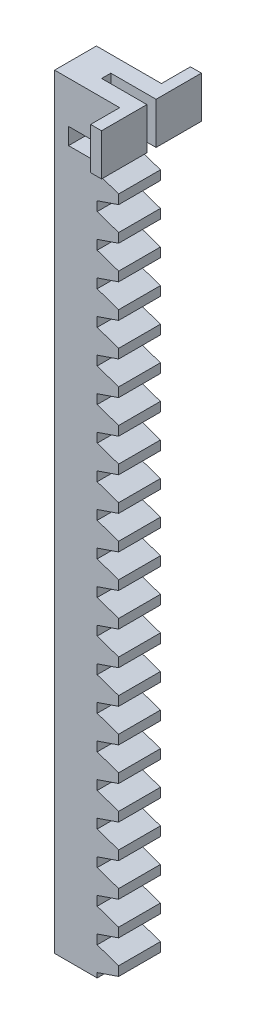
SolidWorks part; units mm, degrees
ref_plane "Plano frontal" through (0, 0, 0) normal (0, 0, 1) x (1, 0, 0)
ref_plane "Plano superior" through (0, 0, 0) normal (0, 1, 0) x (1, 0, 0)
ref_plane "Plano direito" through (0, 0, 0) normal (1, 0, 0) x (0, 0, -1)
sketch "Esboço1" plane through (0, 0, 0) normal (0, 0, 1) x (1, 0, 0)
  line L0 (-2.5965, -162.8747) -> (2.5465, -161.1158)
  line L1 (2.5465, -161.1158) -> (2.5465, -158.8842)
  line L2 (2.5465, -158.8842) -> (-2.5965, -157.1253)
  line L3 (-2.5965, -157.1253) -> (-2.5965, -154.8747)
  line L4 (-2.5965, -154.8747) -> (2.5465, -153.1158)
  line L5 (2.5465, -153.1158) -> (2.5465, -150.8842)
  line L6 (2.5465, -150.8842) -> (-2.5965, -149.1253)
  line L7 (-2.5965, -149.1253) -> (-2.5965, -146.8747)
  line L8 (-2.5965, -146.8747) -> (2.5465, -145.1158)
  line L9 (2.5465, -145.1158) -> (2.5465, -142.8842)
  line L10 (2.5465, -142.8842) -> (-2.5965, -141.1253)
  line L11 (-2.5965, -141.1253) -> (-2.5965, -138.8747)
  line L12 (-2.5965, -138.8747) -> (2.5465, -137.1158)
  line L13 (2.5465, -137.1158) -> (2.5465, -134.8842)
  line L14 (2.5465, -134.8842) -> (-2.5965, -133.1253)
  line L15 (-2.5965, -133.1253) -> (-2.5965, -130.8747)
  line L16 (-2.5965, -130.8747) -> (2.5465, -129.1158)
  line L17 (2.5465, -129.1158) -> (2.5465, -126.8842)
  line L18 (2.5465, -126.8842) -> (-2.5965, -125.1253)
  line L19 (-2.5965, -125.1253) -> (-2.5965, -122.8747)
  line L20 (-2.5965, -122.8747) -> (2.5465, -121.1158)
  line L21 (2.5465, -121.1158) -> (2.5465, -118.8842)
  line L22 (2.5465, -118.8842) -> (-2.5965, -117.1253)
  line L23 (-2.5965, -117.1253) -> (-2.5965, -114.8747)
  line L24 (-2.5965, -114.8747) -> (2.5465, -113.1158)
  line L25 (2.5465, -113.1158) -> (2.5465, -110.8842)
  line L26 (2.5465, -110.8842) -> (-2.5965, -109.1253)
  line L27 (-2.5965, -109.1253) -> (-2.5965, -106.8747)
  line L28 (-2.5965, -106.8747) -> (2.5465, -105.1158)
  line L29 (2.5465, -105.1158) -> (2.5465, -102.8842)
  line L30 (2.5465, -102.8842) -> (-2.5965, -101.1253)
  line L31 (-2.5965, -101.1253) -> (-2.5965, -98.8747)
  line L32 (-2.5965, -98.8747) -> (2.5465, -97.1158)
  line L33 (2.5465, -97.1158) -> (2.5465, -94.8842)
  line L34 (2.5465, -94.8842) -> (-2.5965, -93.1253)
  line L35 (-2.5965, -93.1253) -> (-2.5965, -90.8747)
  line L36 (-2.5965, -90.8747) -> (2.5465, -89.1158)
  line L37 (2.5465, -89.1158) -> (2.5465, -86.8842)
  line L38 (2.5465, -86.8842) -> (-2.5965, -85.1253)
  line L39 (-2.5965, -85.1253) -> (-2.5965, -82.8747)
  line L40 (-2.5965, -82.8747) -> (2.5465, -81.1158)
  line L41 (2.5465, -81.1158) -> (2.5465, -78.8842)
  line L42 (2.5465, -78.8842) -> (-2.5965, -77.1253)
  line L43 (-2.5965, -77.1253) -> (-2.5965, -74.8747)
  line L44 (-2.5965, -74.8747) -> (2.5465, -73.1158)
  line L45 (2.5465, -73.1158) -> (2.5465, -70.8842)
  line L46 (2.5465, -70.8842) -> (-2.5965, -69.1253)
  line L47 (-2.5965, -69.1253) -> (-2.5965, -66.8747)
  line L48 (-2.5965, -66.8747) -> (2.5465, -65.1158)
  line L49 (2.5465, -65.1158) -> (2.5465, -62.8842)
  line L50 (2.5465, -62.8842) -> (-2.5965, -61.1253)
  line L51 (-2.5965, -61.1253) -> (-2.5965, -58.8747)
  line L52 (-2.5965, -58.8747) -> (2.5465, -57.1158)
  line L53 (2.5465, -57.1158) -> (2.5465, -54.8842)
  line L54 (2.5465, -54.8842) -> (-2.5965, -53.1253)
  line L55 (-2.5965, -53.1253) -> (-2.5965, -50.8747)
  line L56 (-2.5965, -50.8747) -> (2.5465, -49.1158)
  line L57 (2.5465, -49.1158) -> (2.5465, -46.8842)
  line L58 (2.5465, -46.8842) -> (-2.5965, -45.1253)
  line L59 (-2.5965, -45.1253) -> (-2.5965, -42.8747)
  line L60 (-2.5965, -42.8747) -> (2.5465, -41.1158)
  line L61 (2.5465, -41.1158) -> (2.5465, -38.8842)
  line L62 (2.5465, -38.8842) -> (-2.5965, -37.1253)
  line L63 (-2.5965, -37.1253) -> (-2.5965, -34.8747)
  line L64 (-2.5965, -34.8747) -> (2.5465, -33.1158)
  line L65 (2.5465, -33.1158) -> (2.5465, -30.8842)
  line L66 (2.5465, -30.8842) -> (-2.5965, -29.1253)
  line L67 (-2.5965, -29.1253) -> (-2.5965, -26.8747)
  line L68 (-2.5965, -26.8747) -> (2.5465, -25.1158)
  line L69 (2.5465, -25.1158) -> (2.5465, -22.8842)
  line L70 (2.5465, -22.8842) -> (-2.5965, -21.1253)
  line L71 (-2.5965, -21.1253) -> (-2.5965, -18.8747)
  line L72 (-2.5965, -18.8747) -> (2.5465, -17.1158)
  line L73 (2.5465, -17.1158) -> (2.5465, -14.8842)
  line L74 (2.5465, -14.8842) -> (-2.5965, -13.1253)
  line L75 (-2.5965, -13.1253) -> (-2.5965, -10.8747)
  line L76 (-2.5965, -10.8747) -> (2.5465, -9.1158)
  line L77 (2.5465, -9.1158) -> (2.5465, -6.8842)
  line L78 (2.5465, -6.8842) -> (-2.5965, -5.1253)
  line L79 (-2.5965, -5.1253) -> (-2.5965, -2.8747)
  line L80 (-2.5965, -2.8747) -> (2.5465, -1.1158)
  line L81 (2.5465, -1.1158) -> (2.5465, 1.1158)
  line L82 (2.5465, 1.1158) -> (-2.5965, 2.8747)
  line L83 (-2.5965, 2.8747) -> (-2.5965, 5.1253)
  line L84 (-2.5965, 5.1253) -> (2.5465, 6.8842)
  line L85 (2.5465, 6.8842) -> (2.5465, 9.1158)
  line L165 (-12.7824, 9.1158) -> (-12.7824, -164)
  line L166 (-12.7824, -164) -> (-2.5965, -164)
  line L167 (-2.5965, -164) -> (-2.5965, -162.8747)
  line L168 (2.5465, 9.1158) -> (-12.7824, 9.1158)
extrude "Ressalto-extrusão1" add sketch "Esboço1" along normal mid plane 10
sketch "Sketch1" plane through (0, 9.1158, 0) normal (0, 1, 0) x (1, 0, 0)
  line L1 (2.7824, 5) -> (-12.7824, 5)
  line L3 (2.7824, -5) -> (-12.7824, -5)
  line L4 (-12.7824, 5) -> (-12.7824, -5)
  line L8 (2.7824, 5) -> (2.7824, 11.9467)
  line L12 (2.7824, -5) -> (2.7824, -11.9508)
  line L13 (-5.4267, 1.1008) -> (2.7824, 1.1008)
  line L14 (-5.4267, 1.1008) -> (-5.4267, -1.1008)
  line L15 (-5.4267, -1.1008) -> (7.7824, -1.1008)
  line L17 (7.7824, 11.9467) -> (2.7824, 11.9467)
  line L18 (2.7824, 1.1008) -> (12.7824, 1.1008)
  line L20 (7.7824, 11.9467) -> (12.7824, 11.9467)
  line L21 (12.7824, 1.1008) -> (12.7824, 11.9467)
  line L22 (7.7824, -1.1008) -> (12.7824, -1.1008)
  line L24 (7.7824, -11.9508) -> (12.7824, -11.9508)
  line L25 (12.7824, -1.1008) -> (12.7824, -11.9508)
  line L26 (7.7824, -11.9508) -> (2.7824, -11.9508)
  point P0 (0, 0)
  point P13 (12.7824, 0)
  dimension "D1" = 10
  dimension "D2" = 5
  dimension "D3" = 5
  dimension "D4" = 5
  dimension "D5" = 5
  dimension "D7" = 10.8459
  dimension "D8" = 10.85
extrude "Boss-Extrude1" add sketch "Sketch1" along normal blind 10
sketch "Sketch2" plane through (0, 19.1158, 0) normal (0, 1, 0) x (1, 0, 0)
  line L1 (10.6166, 13.0514) -> (13.4454, 13.0514)
  line L3 (10.6166, -14.7937) -> (13.4454, -14.7937)
  line L4 (13.4454, 13.0514) -> (13.4454, -14.7937)
  line L5 (10.6166, 13.0514) -> (5.402, 13.0514)
  line L7 (10.6166, -14.7937) -> (5.402, -14.7937)
  line L8 (5.402, 13.0514) -> (5.402, -14.7937)
extrude "Cut-Extrude1" cut sketch "Sketch2" against normal blind 50
sketch "Sketch3" plane through (2.5465, 0, 0) normal (1, 0, 0) x (0, 0, -1)
  line L1 (-5, 9.1158) -> (5, 9.1158)
  line L2 (-5, 9.1158) -> (-5, 5.1253)
  line L3 (-5, 5.1253) -> (5, 5.1253)
  line L4 (5, 9.1158) -> (5, 5.1253)
extrude "Cut-Extrude2" cut sketch "Sketch3" against normal blind 12
